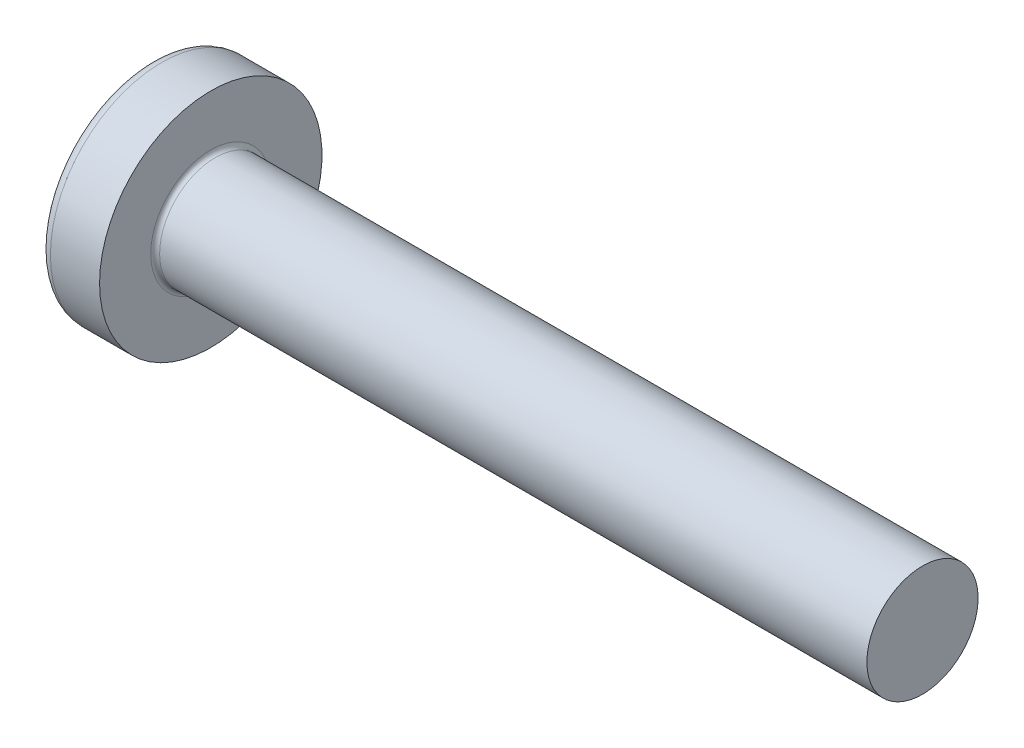
SolidWorks part; units mm, degrees
ref_plane "Plane1" through (0, 0, 0) normal (0, 0, 1) x (1, 0, 0)
ref_plane "Plane2" through (0, 0, 0) normal (0, 1, 0) x (1, 0, 0)
ref_plane "Plane3" through (0, 0, 0) normal (1, 0, 0) x (0, 0, -1)
sketch "BodySke" plane through (0, 0, 0) normal (0, 0, 1) x (1, 0, 0)
  line L0 (2.1, 1.25) -> (2.1, 2.5)
  line L1 (2.325, 6.35) -> (2.325, -3.175) construction
  line L2 (-25.4, 0) -> (127, 0) construction
  line L3 (18.1, 0) -> (0, 0)
  line L4 (2.1, 1.25) -> (18.1, 1.25)
  line L5 (18.1, 1.25) -> (18.1, 0)
  line L6 (0.995, 2.5) -> (2.1, 2.5)
  line L8 (2.1, 6.35) -> (2.1, -3.175) construction
  arc A0 (0.8032, 2.4043) -> (0, 0) centre (4, 0) ccw
  arc A2 (0.8032, 2.4043) -> (0.995, 2.5) centre (0.995, 2.26) cw
  dimension "Head_fillet_rad" = 0.24
  dimension "Head_crown_rad" = 4
  dimension "Head_ht" = 2.1
  dimension "Diameter" = 2.5
  dimension "Length" = 16
  dimension "Head_dia" = 5
  dimension "Advance" = 0.45
  dimension "Thread_nom" = 16
revolve "Base-Revolve" add sketch "BodySke"
cosmetic thread "ThreadCosmetic" [suppressed]
fillet "Fillet1" radius 0.1 1 edges at (2.1, 0, 1.25)
sketch "Sketch3" plane through (0, 0, 0) normal (1, 0, 0) x (0, 0, -1)
  line L0 (0.37, -1.3) -> (-0.37, -1.3)
  line L1 (0.37, -1.3) -> (0.37, 1.3)
  line L2 (-0.37, 1.3) -> (0.37, 1.3)
  line L3 (-0.37, 1.3) -> (-0.37, -1.3)
  dimension "D1" = 1.05
  dimension "Cross_dia" = 2.6
  dimension "D2" = 0.24
  dimension "Cross_width" = 0.74
ref_plane "Plane4" through (1.5, 0, 0) normal (1, 0, 0) x (0, 0, -1)
sketch "Sketch4" plane through (1.5, 0, 0) normal (1, 0, 0) x (0, 0, -1)
  line L0 (0.37, -0.5521) -> (-0.37, -0.5521)
  line L1 (0.37, -0.5521) -> (0.37, 0.5521)
  line L2 (-0.37, 0.5521) -> (0.37, 0.5521)
  line L3 (-0.37, 0.5521) -> (-0.37, -0.5521)
  dimension "D1" = 0.48
  dimension "D2" = 0.684
  dimension "D3" = 0.24
  dimension "D4" = 0.342
loft "Recess" cut profiles "Sketch3", "Sketch4"
pattern_circular "RecPat" count 2 every 90 about axis through (0, 0, 0) along (1, 0, 0) of "Recess"
sketch "RecCorSke" plane through (0, 0, 0) normal (0, 0, 1) x (1, 0, 0)
  line L0 (-3.175, 0) -> (15.875, 0) construction
  line L1 (-25.4, 0) -> (127, 0) construction
  line L2 (0, 0) -> (0, 0.6609)
  line L3 (0, 0.6609) -> (1.5, 0.556)
  line L4 (1.5, 0.556) -> (1.6807, 0)
  line L5 (1.6807, 0) -> (0, 0)
  dimension "Diameter" = 1.112
  dimension "Depth" = 1.42
  dimension "Draft_angle" = 4
  dimension "Bottom_angle" = 18
revolve "RecessCore" cut sketch "RecCorSke" angle 360 about L0
sketch "ThdSchSke" plane through (0, 0, 0) normal (0, 0, 1) x (1, 0, 0)
  line L0 (3, -0.9965) -> (2.8225, -1.25)
  line L1 (3, -0.9965) -> (3.1775, -1.25)
  line L2 (3.1775, -1.25) -> (3.1775, -1.5625)
  line L3 (-3.175, 0) -> (5.1513, 0) construction
  line L5 (3.1775, -1.5625) -> (2.8225, -1.5625)
  line L6 (2.8225, -1.5625) -> (2.8225, -1.25)
  dimension "Thread_minor" = 1.548
  dimension "Diameter" = 2
  dimension "Start" = 2.4
  dimension "SideAngle" = 55
  dimension "VeeAngle" = 70
  dimension "Overcut" = 2.5
revolve "ThreadSchematic" [suppressed] cut sketch "ThdSchSke" angle 360 about L3
pattern_linear "ThdSchPat" [suppressed]
equation "\"D1@Sketch3\" = \"Cross_dia@Sketch3\" / 2"
equation "\"D2@Sketch3\" = \"Cross_width@Sketch3\" / 2"
equation "\"Depth@RecCorSke\" = \"Cross_depth@Plane4\""
equation "\"D1@Sketch4\" = \"Cross_width@Sketch3\""
equation "\"D2@Sketch4\" = \"Cross_dia@Sketch3\" - 2.0 * \"Cross_depth@Plane4\" * tan(26.5  * 0.017453292)"
equation "\"D3@Sketch4\" = \"D1@Sketch4\" / 2"
equation "\"D4@Sketch4\" = \"D2@Sketch4\" / 2"
equation "\"Thread_length@ThreadCosmetic\" = ((sgn( (\"Length@BodySke\" - \"Advance@BodySke\" * 2.0 ) - \"Thread_nom@BodySke\" )-1)*( (\"Length@BodySke\" - \"Advance@BodySke\" * 2.0 ) - \"Thread_nom@BodySke\" ))/-2+ \"Thread_nom@BodySke\""
equation "\"Thread_minor@ThdSchSke\" = \"Thread_minor@ThreadCosmetic\""
equation "\"Diameter@ThdSchSke\" = \"Diameter@BodySke\""
equation "\"Overcut@ThdSchSke\" = \"Diameter@BodySke\" * 1.25"
equation "\"Start@ThdSchSke\" = \"Head_ht@BodySke\" + \"Length@BodySke\" - \"Thread_length@ThreadCosmetic\"  '---Non-countersunk---"
equation "\"Num_threads@ThdSchPat\" = int( \"Thread_length@ThreadCosmetic\" / \"Advance@BodySke\" + 0.999 )  + 1"
equation "\"Advance@ThdSchPat\" = \"Thread_length@ThreadCosmetic\" /  (\"Num_threads@ThdSchPat\" - 1) 'relax it"
